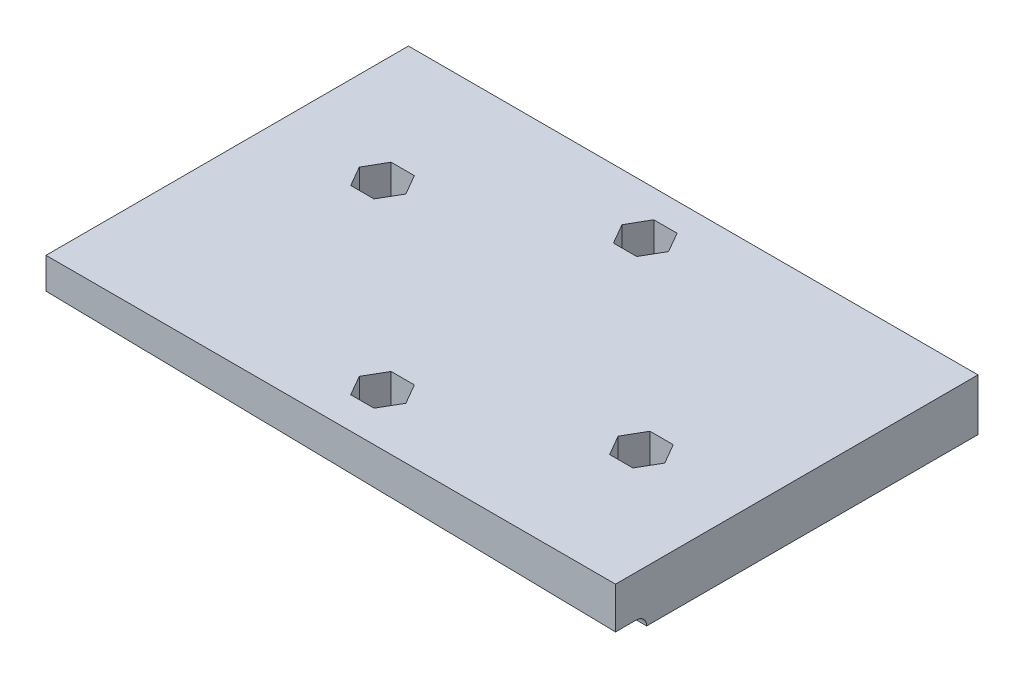
SolidWorks part; units mm, degrees
ref_plane "Front Plane" through (0, 0, 0) normal (0, 0, 1) x (1, 0, 0)
ref_plane "Top Plane" through (0, 0, 0) normal (0, 1, 0) x (1, 0, 0)
ref_plane "Right Plane" through (0, 0, 0) normal (1, 0, 0) x (0, 0, -1)
sketch "Sketch1" plane through (0, 0, 0) normal (0, 1, 0) x (1, 0, 0)
  line L1 (-45.1306, -30.6096) -> (64.8694, -30.6096)
  line L2 (-45.1306, -30.6096) -> (-45.1306, 39.3904)
  line L3 (-45.1306, 39.3904) -> (64.8694, 39.3904)
  line L4 (64.8694, -30.6096) -> (64.8694, 39.3904)
  dimension "D1" = 70
  dimension "D2" = 110
extrude "Boss-Extrude1" add sketch "Sketch1" along normal blind 10 contours L2 L1 L4 L3
sketch "Sketch6" plane through (0, 0, 0) normal (0, -1, 0) x (1, 0, 0)
  line L0 (64.8694, -4.3904) -> (9.8694, -4.3904)
  line L1 (64.8694, 30.6096) -> (64.8694, -39.3904) construction
  line L2 (9.8694, -4.3904) -> (9.8694, 20.6096)
  line L5 (9.8694, -4.3904) -> (9.8694, -30.1287)
  dimension "D1" = 55
  dimension "D2" = 25
sketch "Sketch15" plane through (0, 0, 0) normal (0, -1, 0) x (1, 0, 0)
  line L0 (9.8694, -4.3904) -> (-25.1306, -4.3904)
  line L1 (-25.1306, -4.3904) -> (44.8694, -4.3904)
sketch "Sketch5" plane through (0, 10, 0) normal (0, 1, 0) x (1, 0, 0)
  circle A0 centre (9.8694, -20.6096) radius 1.9
  dimension "D1" = 3.8
extrude "Cut-Extrude4" cut sketch "Sketch5" against normal through all
sketch "Sketch10" plane through (-45.1306, 0, 0) normal (-1, 0, 0) x (0, 0, 1)
  line L0 (30.6096, 0) -> (30.6096, 4)
  line L1 (30.6096, 10) -> (30.6096, 0) construction
  line L2 (30.6096, 4) -> (30.4899, 3.8725)
  line L3 (30.6096, 0) -> (24.6096, 0)
  line L4 (30.6096, 0) -> (-39.3904, 0) construction
  line L5 (24.6096, 0) -> (24.6096, 4)
  line L6 (24.6096, 4) -> (30.6096, 4)
sketch "Sketch12" plane through (64.8694, 0, 0) normal (1, 0, 0) x (0, 0, -1)
  line L0 (-30.6096, 0) -> (-30.6096, 2)
  line L1 (-30.6096, 10) -> (-30.6096, 0) construction
  line L2 (-30.6096, 2) -> (-24.6096, 2)
  line L3 (-24.6096, 2) -> (-24.6096, 0)
  line L4 (-30.6096, 0) -> (39.3904, 0) construction
  line L5 (-24.6096, 0) -> (-30.6096, 0)
sketch "Sketch14" plane through (0, 0, 30.6096) normal (0, 0, 1) x (1, 0, 0)
  line L0 (-45.1306, 0) -> (-45.1306, 4)
  line L1 (-45.1306, 4) -> (64.8694, 2)
  line L2 (64.8694, 2) -> (64.8694, 0)
  line L3 (64.8694, 0) -> (-45.1306, 0)
extrude "Cut-Extrude6" cut sketch "Sketch14" against normal blind 6
sketch "Sketch17" plane through (0, 0, 0) normal (0, -1, 0) x (-1, 0, 0)
  circle A0 centre (-9.8694, 30.1287) radius 1.9
  dimension "D1" = 3.8
extrude "Cut-Extrude8" cut sketch "Sketch17" against normal through all
sketch "Sketch22" plane through (0, 0, 0) normal (0, -1, 0) x (-1, 0, 0)
  line L0 (-44.8694, 4.3904) -> (-44.8694, -5.6096)
  dimension "D1" = 10
sketch "Sketch23" plane through (0, 0, 0) normal (0, -1, 0) x (-1, 0, 0)
  line L0 (25.1306, 4.3904) -> (25.1306, 14.3904)
  dimension "D1" = 10
fillet "Fillet1" radius 2 1 edges at (9.8694, 3, 24.6096)
sketch "Sketch24" plane through (0, 0, 0) normal (0, -1, 0) x (1, 0, 0)
  circle A0 centre (44.8694, 5.6096) radius 1.9
  dimension "D1" = 3.8
extrude "Cut-Extrude12" cut sketch "Sketch24" against normal through all
sketch "Sketch25" plane through (0, 0, 0) normal (0, -1, 0) x (1, 0, 0)
  circle A0 centre (-25.1306, -14.3904) radius 1.9
  dimension "D1" = 3.8
extrude "Cut-Extrude13" cut sketch "Sketch25" against normal through all
ref_plane "Plane1" through (0, -5, 0) normal (0, 1, 0) x (1, 0, 0)
sketch "Sketch27" plane through (0, 10, 0) normal (0, 1, 0) x (1, 0, 0)
  line L1 (14.3694, 30.1287) -> (12.1194, 34.0258)
  line L2 (12.1194, 34.0258) -> (7.6194, 34.0258)
  line L3 (7.6194, 34.0258) -> (5.3694, 30.1287)
  line L4 (5.3694, 30.1287) -> (7.6194, 26.2316)
  line L5 (7.6194, 26.2316) -> (12.1194, 26.2316)
  line L6 (12.1194, 26.2316) -> (14.3694, 30.1287)
  circle A0 centre (9.8694, 30.1287) radius 3.8971 construction
  dimension "D1" = 9
sketch "Sketch30" plane through (0, 10, 0) normal (0, 1, 0) x (1, 0, 0)
  line L2 (49.3694, -5.6096) -> (47.1194, -1.7125)
  line L3 (47.1194, -1.7125) -> (42.6194, -1.7125)
  line L4 (42.6194, -1.7125) -> (40.3694, -5.6096)
  line L5 (40.3694, -5.6096) -> (42.6194, -9.5068)
  line L6 (42.6194, -9.5068) -> (47.1194, -9.5068)
  line L7 (47.1194, -9.5068) -> (49.3694, -5.6096)
  circle A0 centre (44.8694, -5.6096) radius 3.8971 construction
  dimension "D1" = 9
sketch "Sketch31" plane through (0, 10, 0) normal (0, 1, 0) x (1, 0, 0)
  line L1 (14.3694, -20.6096) -> (12.1194, -16.7125)
  line L2 (12.1194, -16.7125) -> (7.6194, -16.7125)
  line L3 (7.6194, -16.7125) -> (5.3694, -20.6096)
  line L4 (5.3694, -20.6096) -> (7.6194, -24.5068)
  line L5 (7.6194, -24.5068) -> (12.1194, -24.5068)
  line L6 (12.1194, -24.5068) -> (14.3694, -20.6096)
  circle A0 centre (9.8694, -20.6096) radius 3.8971 construction
  dimension "D1" = 9
sketch "Sketch32" plane through (0, 10, 0) normal (0, 1, 0) x (1, 0, 0)
  line L1 (-20.6306, 14.3904) -> (-22.8806, 18.2875)
  line L2 (-22.8806, 18.2875) -> (-27.3806, 18.2875)
  line L3 (-27.3806, 18.2875) -> (-29.6306, 14.3904)
  line L4 (-29.6306, 14.3904) -> (-27.3806, 10.4932)
  line L5 (-27.3806, 10.4932) -> (-22.8806, 10.4932)
  line L6 (-22.8806, 10.4932) -> (-20.6306, 14.3904)
  circle A0 centre (-25.1306, 14.3904) radius 3.8971 construction
  point P1 (0, 0)
  dimension "D1" = 9
extrude "Cut-Extrude15" cut sketch "Sketch27" against normal blind 6
extrude "Cut-Extrude16" cut sketch "Sketch30" against normal blind 6
extrude "Cut-Extrude17" cut sketch "Sketch31" against normal blind 6
extrude "Cut-Extrude18" cut sketch "Sketch32" against normal blind 6
